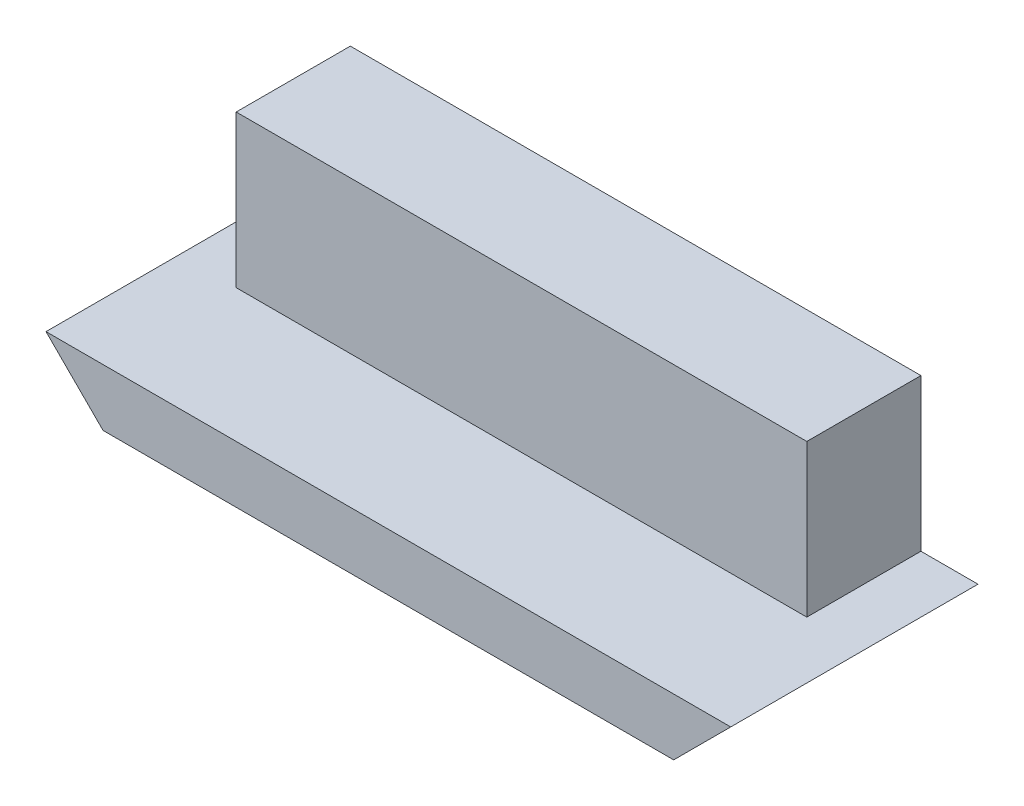
SolidWorks part; units mm, degrees
ref_plane "Front Plane" through (0, 0, 0) normal (0, 0, 1) x (1, 0, 0)
ref_plane "Top Plane" through (0, 0, 0) normal (0, 1, 0) x (1, 0, 0)
ref_plane "Right Plane" through (0, 0, 0) normal (1, 0, 0) x (0, 0, -1)
sketch "Sketch1" plane through (0, 0, 0) normal (0, 0, 1) x (1, 0, 0)
  line L0 (0, 0) -> (-1.5, 1.5)
  line L1 (0, 0) -> (15, 0)
  line L2 (0, 1.5) -> (0, 5.5)
  line L3 (0, 5.5) -> (15, 5.5)
  line L4 (15, 1.5) -> (15, 5.5)
  line L5 (-1.5, 1.5) -> (0, 1.5)
  line L6 (7.5, 5.5) -> (7.5, 0) construction
  line L7 (15, 0) -> (16.5, 1.5)
  line L8 (16.5, 1.5) -> (15, 1.5)
  dimension "D1" = 15
  dimension "D2" = 5.5
  dimension "D3" = 1.5
  dimension "D4" = 1.5
extrude "Boss-Extrude1" add sketch "Sketch1" along normal blind 6.5
sketch "Sketch2" plane through (0, 0, 6.5) normal (0, 0, 1) x (1, 0, 0)
  line L1 (0, 1.5) -> (15, 1.5)
  line L2 (0, 1.5) -> (0, 5.5)
  line L3 (0, 5.5) -> (15, 5.5)
  line L4 (15, 1.5) -> (15, 5.5)
extrude "Cut-Extrude1" cut sketch "Sketch2" against normal offset from surface (3.5 mm away) 3 up to face at (7.5, 2.125, 0)
